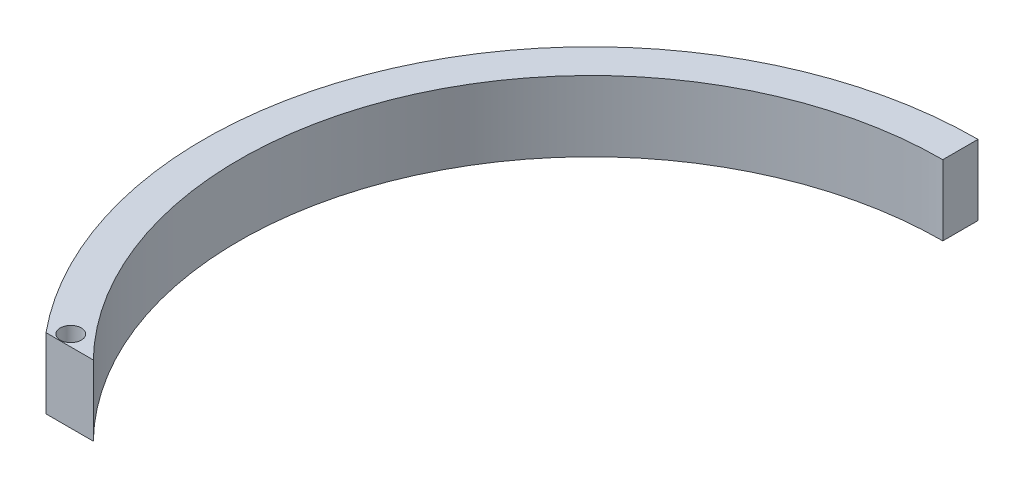
SolidWorks part; units mm, degrees
material "1060 Alloy"
ref_plane "Front Plane" through (0, 0, 0) normal (0, 0, 1) x (1, 0, 0)
ref_plane "Top Plane" through (0, 0, 0) normal (0, 1, 0) x (1, 0, 0)
ref_plane "Right Plane" through (0, 0, 0) normal (1, 0, 0) x (0, 0, -1)
sketch "Sketch2" plane through (0, 0, 0) normal (0, 1, 0) x (1, 0, 0)
  line L0 (0, 55) -> (0, -55) construction
  line L1 (-42.4264, -35) -> (67.4793, -35) construction
  line L2 (0, 55) -> (0, 50)
  line L3 (-35.7071, -35) -> (-42.4264, -35)
  line L4 (-42.4264, -35) -> (-38.5695, -31.8182) construction
  arc A0 (0, 50) -> (-35.7071, -35) centre (0, 0) ccw
  arc A1 (0, 55) -> (-42.4264, -35) centre (0, 0) ccw
  circle A2 centre (-40.4979, -33.4091) radius 1.5
  dimension "D1" = 100
  dimension "D2" = 110
  dimension "D4" = 3
  dimension "D3" = 90
extrude "Boss-Extrude1" add sketch "Sketch2" along normal blind 10
